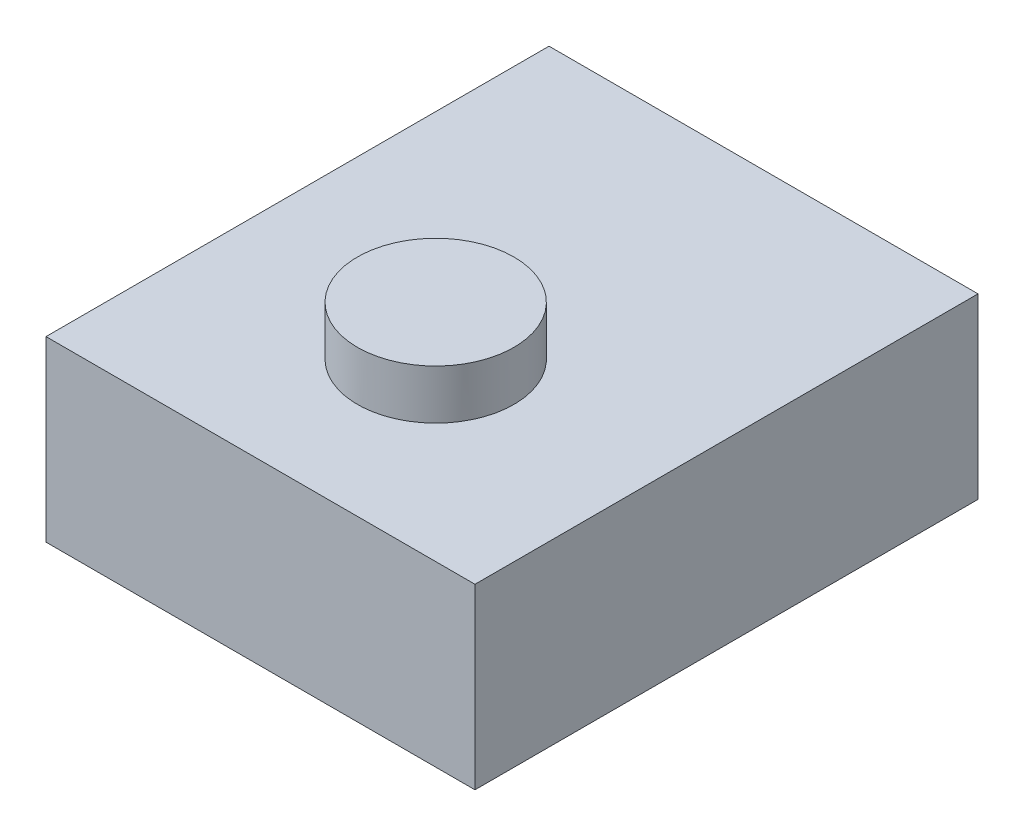
SolidWorks part; units mm, degrees
ref_plane "Front Plane" through (0, 0, 0) normal (0, 0, 1) x (1, 0, 0)
ref_plane "Top Plane" through (0, 0, 0) normal (0, 1, 0) x (1, 0, 0)
ref_plane "Right Plane" through (0, 0, 0) normal (1, 0, 0) x (0, 0, -1)
sketch "Sketch2" plane through (0, 0, 0) normal (0, 1, 0) x (1, 0, 0)
  line L1 (0, 0) -> (15.18, 0)
  line L2 (0, 0) -> (0, 17.8)
  line L3 (0, 17.8) -> (15.18, 17.8)
  line L4 (15.18, 0) -> (15.18, 17.8)
  dimension "D1" = 17.8
  dimension "D2" = 15.18
extrude "Boss-Extrude1" add sketch "Sketch2" along normal blind 6.3
sketch "Sketch3" plane through (0, 6.3, 0) normal (0, 1, 0) x (1, 0, 0)
  line L0 (7.59, 0) -> (7.59, 6.2) construction
  line L1 (0, 0) -> (15.18, 0) construction
  circle A0 centre (7.59, 6.2) radius 2.77
  dimension "D1" = 5.54
  dimension "D2" = 6.2
extrude "Boss-Extrude2" add sketch "Sketch3" along normal blind 1.75
